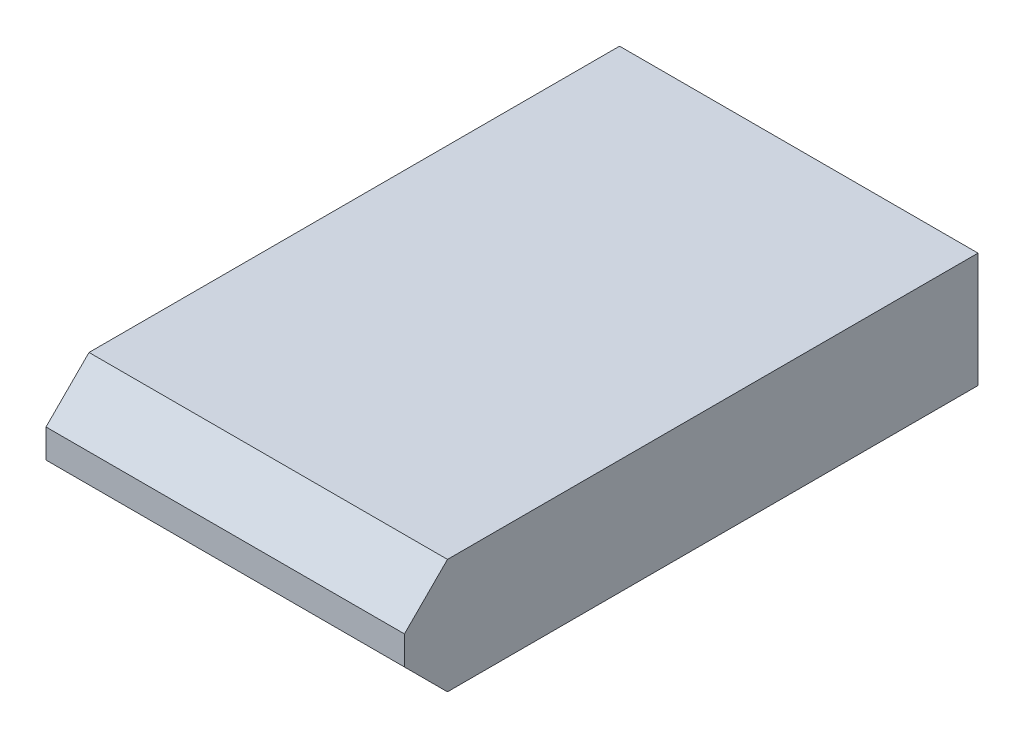
SolidWorks part; units mm, degrees
ref_plane "前视基准面" through (0, 0, 0) normal (0, 0, 1) x (1, 0, 0)
ref_plane "上视基准面" through (0, 0, 0) normal (0, 1, 0) x (1, 0, 0)
ref_plane "右视基准面" through (0, 0, 0) normal (1, 0, 0) x (0, 0, -1)
other "Configuration Table"
sketch "草图1" plane through (0, 0, 0) normal (0, 1, 0) x (1, 0, 0)
  line L1 (0, 0) -> (25, 0)
  line L2 (0, 0) -> (0, 40)
  line L3 (0, 40) -> (25, 40)
  line L4 (25, 0) -> (25, 40)
  dimension "D1" = 40
  dimension "D2" = 25
extrude "凸台-拉伸1" add sketch "草图1" along normal blind 8
chamfer "倒角1" distance 3 angle 45 2 edges at (12.5, 0, 0) (12.5, 8, 0)
